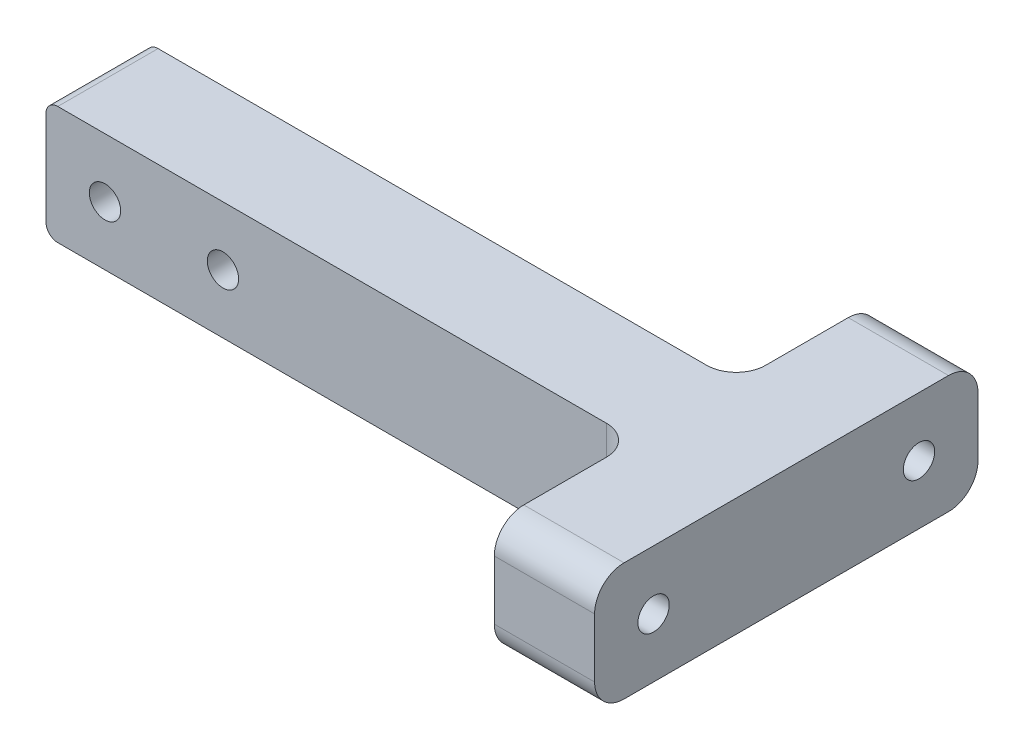
SolidWorks part; units mm, degrees
material "Acetal-Delrin 100 Black"
ref_plane "Front Plane" through (0, 0, 0) normal (0, 0, 1) x (1, 0, 0)
ref_plane "Top Plane" through (0, 0, 0) normal (0, 1, 0) x (1, 0, 0)
ref_plane "Right Plane" through (0, 0, 0) normal (1, 0, 0) x (0, 0, -1)
sketch "Sketch1" plane through (0, 0, 0) normal (0, 1, 0) x (1, 0, 0)
  line L0 (0, 10.795) -> (0, -10.795)
  line L1 (0, -10.795) -> (127, -10.795)
  line L2 (127, -10.795) -> (127, -41.275)
  line L3 (127, -41.275) -> (148.59, -41.275)
  line L4 (148.59, -41.275) -> (148.59, 41.275)
  line L5 (148.59, 41.275) -> (127, 41.275)
  line L6 (127, 41.275) -> (127, 10.795)
  line L7 (127, 10.795) -> (0, 10.795)
  line L8 (0, 0) -> (148.59, 0) construction
  point P9 (148.59, 0)
  point P12 (0, 0)
  dimension "D1" = 21.59
  dimension "D2" = 82.55
  dimension "D3" = 21.59
  dimension "D4" = 127
extrude "Boss-Extrude1" add sketch "Sketch1" along normal blind 25.4
fillet "Fillet1" radius 6.35 2 edges at (127, 12.7, 10.795) (127, 12.7, -10.795)
sketch "Sketch2" plane through (0, 0, 10.795) normal (0, 0, 1) x (1, 0, 0)
  line L0 (0, 25.4) -> (0, 0) construction
  line L1 (25.4, 25.4) -> (25.4, 0) construction
  line L2 (0, 25.4) -> (120.65, 25.4) construction
  line L3 (0, 0) -> (120.65, 0) construction
  line L4 (0, 12.7) -> (38.1, 12.7) construction
  circle A0 centre (12.7, 12.7) radius 3.3734
  circle A1 centre (38.1, 12.7) radius 3.3734
  point P0 (0, 12.7)
  dimension "D4" = 6.7469
  dimension "D1" = 25.4
  dimension "D2" = 12.7
  dimension "D3" = 12.7
extrude "Cut-Extrude1" cut sketch "Sketch2" against normal through all
sketch "Sketch3" plane through (148.59, 0, 0) normal (1, 0, 0) x (0, 0, -1)
  line L0 (-41.275, 25.4) -> (-41.275, 0) construction
  line L1 (-41.275, 25.4) -> (41.275, 25.4) construction
  line L2 (-41.275, 12.7) -> (41.275, 12.7) construction
  line L3 (41.275, 25.4) -> (41.275, 0) construction
  line L4 (0, 25.4) -> (0, 0) construction
  circle A0 centre (-28.575, 12.7) radius 3.3734
  circle A1 centre (28.575, 12.7) radius 3.3734
  point P0 (-41.275, 12.7)
  point P1 (0, 25.4)
  dimension "D1" = 6.7469
  dimension "D2" = 57.15
extrude "Cut-Extrude2" cut sketch "Sketch3" against normal through all
fillet "Fillet2" radius 6.35 4 edges at (137.795, 25.4, -41.275) (137.795, 0, -41.275) (137.795, 25.4, 41.275) (137.795, 0, 41.275)
fillet "Fillet3" radius 2.54 2 edges at (0, 0, 0) (0, 25.4, 0)
